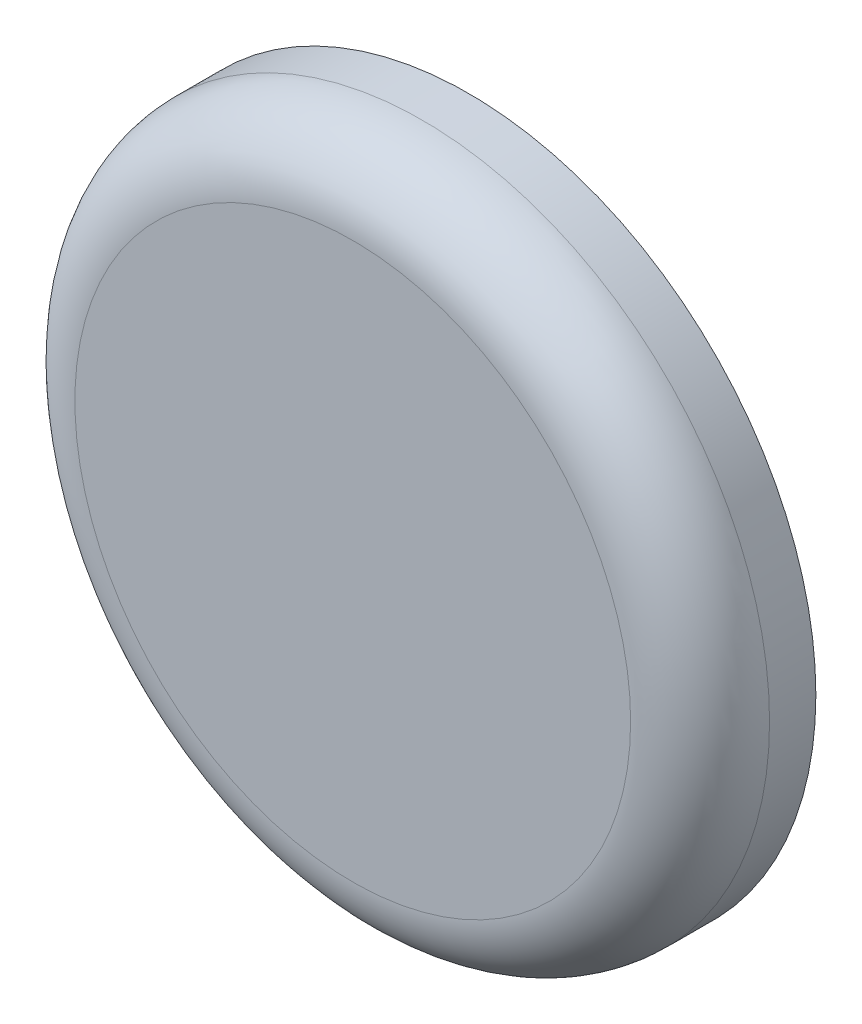
SolidWorks part; units mm, degrees
ref_plane "Front Plane" through (0, 0, 0) normal (0, 0, 1) x (1, 0, 0)
ref_plane "Top Plane" through (0, 0, 0) normal (0, 1, 0) x (1, 0, 0)
ref_plane "Right Plane" through (0, 0, 0) normal (1, 0, 0) x (0, 0, -1)
sketch "Sketch1" plane through (0, 0, 0) normal (0, 0, 1) x (1, 0, 0)
  circle A0 centre (0, 0) radius 15
extrude "Boss-Extrude1" add sketch "Sketch1" along normal blind 5
fillet "Fillet1" radius 3 1 edges at (15, 0, 5)
